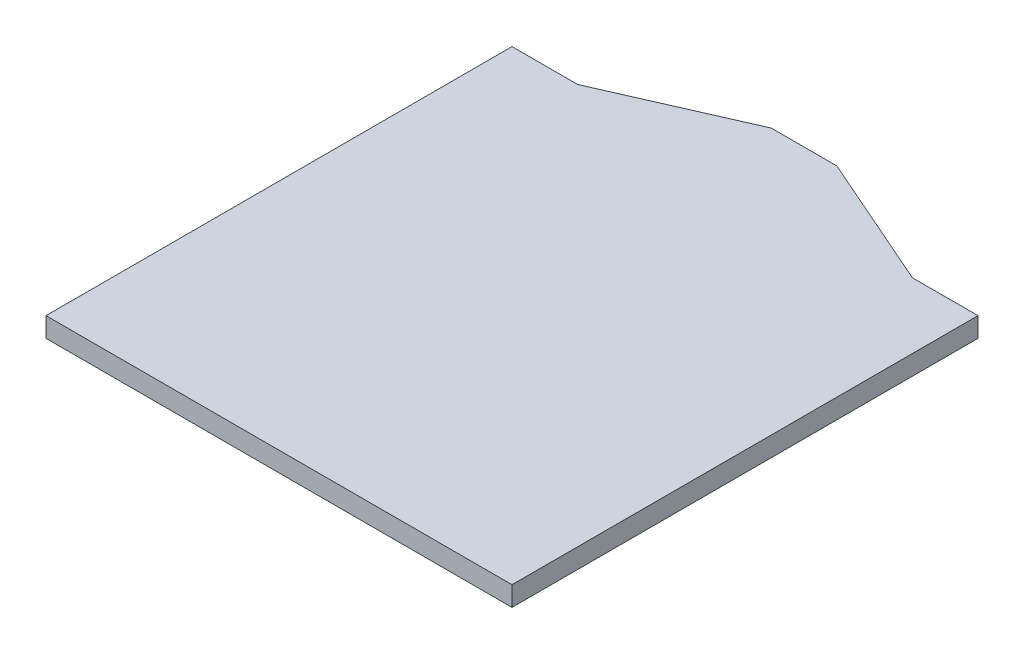
SolidWorks part; units mm, degrees
ref_plane "Front Plane" through (0, 0, 0) normal (0, 0, 1) x (1, 0, 0)
ref_plane "Top Plane" through (0, 0, 0) normal (0, 1, 0) x (1, 0, 0)
ref_plane "Right Plane" through (0, 0, 0) normal (1, 0, 0) x (0, 0, -1)
sketch "Sketch1" plane through (0, 0, 0) normal (0, 1, 0) x (1, 0, 0)
  line L0 (-35.5, 35.5) -> (-25.5, 35.5)
  line L1 (-35.5, 35.5) -> (35.5, 35.5)
  line L2 (-35.5, 35.5) -> (-35.5, -35.5)
  line L3 (-35.5, -35.5) -> (35.5, -35.5)
  line L4 (35.5, 35.5) -> (35.5, -35.5)
  line L5 (-25.5, 35.5) -> (-5, 44.5)
  line L6 (-5, 44.5) -> (5, 44.5)
  line L7 (5, 44.5) -> (25.5, 35.5)
  line L8 (25.5, 35.5) -> (35.5, 35.5)
  point P4 (-35.5, 0)
  point P6 (0, -35.5)
  point P11 (0, 44.5)
  point P12 (0, 35.5)
  point P13 (0, 0)
  point P14 (0, 0)
  dimension "D1" = 71
  dimension "D2" = 71
  dimension "D3" = 10
  dimension "D4" = 80
  dimension "D5" = 10
  dimension "D6" = 10
extrude "Boss-Extrude1" add sketch "Sketch1" along normal blind 3 contours L7 L6 L5 L1 | L4 L1 L0 L2 L3
